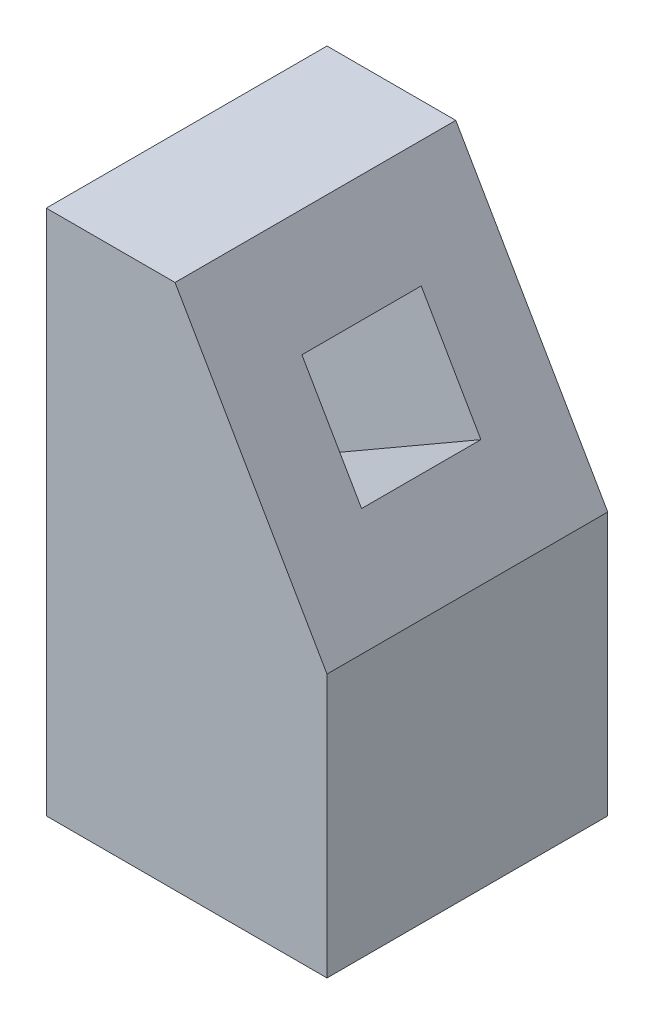
SolidWorks part; units mm, degrees
ref_plane "前视基准面" through (0, 0, 0) normal (0, 0, 1) x (1, 0, 0)
ref_plane "上视基准面" through (0, 0, 0) normal (0, 1, 0) x (1, 0, 0)
ref_plane "右视基准面" through (0, 0, 0) normal (1, 0, 0) x (0, 0, -1)
other "Configuration Table"
sketch "草图1" plane through (0, 0, 0) normal (0, 1, 0) x (1, 0, 0)
  line L0 (4, 0) -> (4, 8) construction
  line L1 (0, 0) -> (8, 0)
  line L2 (0, 0) -> (0, 8)
  line L3 (0, 8) -> (8, 8)
  line L4 (8, 0) -> (8, 8)
  dimension "D1" = 8
  dimension "D2" = 8
extrude "凸台-拉伸1" add sketch "草图1" along normal blind 15
sketch "草图2" plane through (0, 0, -8) normal (0, 0, -1) x (-1, 0, 0)
  line L0 (-8, 7.5) -> (-3.6699, 15)
  line L1 (-8, 15) -> (-8, 0) construction
  line L2 (-8, 15) -> (0, 15) construction
  line L3 (-3.6699, 15) -> (-8, 15)
  line L4 (-8, 15) -> (-8, 7.5)
  dimension "D1" = 30
  dimension "D2" = 7.5
extrude "切除-拉伸1" cut sketch "草图2" against normal up to next
sketch "草图3" plane through (9.2476, 5.3391, 0) normal (0.866, 0.5, 0) x (0, 0, -1)
  line L0 (0, 6.8253) -> (8, 6.8253) construction
  line L1 (0, 11.1554) -> (0, 2.4952) construction
  line L2 (8, 2.4952) -> (8, 11.1554) construction
  line L3 (4, 3.6037) -> (4, 7.0371) construction
  line L4 (5.7, 8.5253) -> (2.3, 8.5253)
  line L5 (2.3, 8.5253) -> (2.3, 5.1253)
  line L6 (5.7, 8.5253) -> (5.7, 5.1253)
  line L7 (5.7, 5.1253) -> (2.3, 5.1253)
  point P7 (4, 6.8253)
  point P14 (4, 8.5253)
  point P15 (5.7, 6.8253)
  point P16 (2.3, 6.8253)
  dimension "D1" = 1.7
  dimension "D2" = 1.7
extrude "切除-拉伸2" cut sketch "草图3" against normal blind 10
